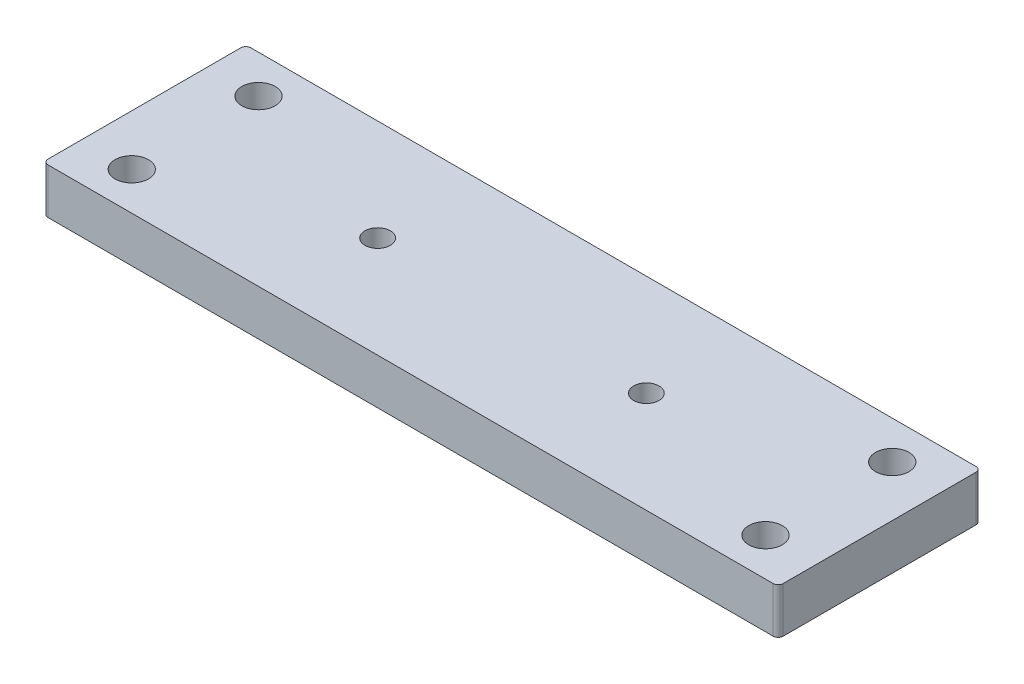
SolidWorks part; units mm, degrees
ref_plane "Front Plane" through (0, 0, 0) normal (0, 0, 1) x (1, 0, 0)
ref_plane "Top Plane" through (0, 0, 0) normal (0, 1, 0) x (1, 0, 0)
ref_plane "Right Plane" through (0, 0, 0) normal (1, 0, 0) x (0, 0, -1)
sketch "Sketch1" plane through (0, 0, 0) normal (0, 1, 0) x (1, 0, 0)
  line L0 (13.6936, 0) -> (141.0915, 0) construction
  line L5 (0, 0) -> (0, -70.4236) construction
  line L7 (33.5, -8) -> (-33.5, -8) construction
  line L8 (33.5, -8) -> (33.5, 8) construction
  line L9 (33.5, 8) -> (-33.5, 8) construction
  line L10 (-33.5, -8) -> (-33.5, 8) construction
  line L11 (33.5, -8) -> (-33.5, 8) construction
  line L12 (33.5, 8) -> (-33.5, -8) construction
  line L13 (-72.5, -20) -> (72.5, -20)
  line L14 (-72.5, -20) -> (-72.5, 20)
  line L15 (-72.5, 20) -> (72.5, 20)
  line L16 (72.5, -20) -> (72.5, 20)
  line L17 (-72.5, -20) -> (72.5, 20) construction
  line L18 (-72.5, 20) -> (72.5, -20) construction
  circle A0 centre (26.5, 0) radius 2.5
  circle A1 centre (62.5, -12.5) radius 3.3
  circle A2 centre (62.5, 12.5) radius 3.3
  circle A11 centre (-26.5, 0) radius 2.5
  circle A12 centre (-62.5, 12.5) radius 3.3
  circle A13 centre (-62.5, -12.5) radius 3.3
  point P0 (0, 0)
  point P13 (0, 0)
  dimension "D5" = 5
  dimension "D7" = 6.6
  dimension "D2" = 145
  dimension "D3" = 40
  dimension "D6" = 26.5
  dimension "D8" = 62.5
  dimension "D9" = 12.5
  dimension "D10" = 67
  dimension "D11" = 16
  dimension "D12" = 2
extrude "Boss-Extrude1" add sketch "Sketch1" along normal blind 9
fillet "Fillet1" radius 1 4 edges at (72.5, 4.5, -20) (72.5, 4.5, 20) (-72.5, 4.5, -20) (-72.5, 4.5, 20)
